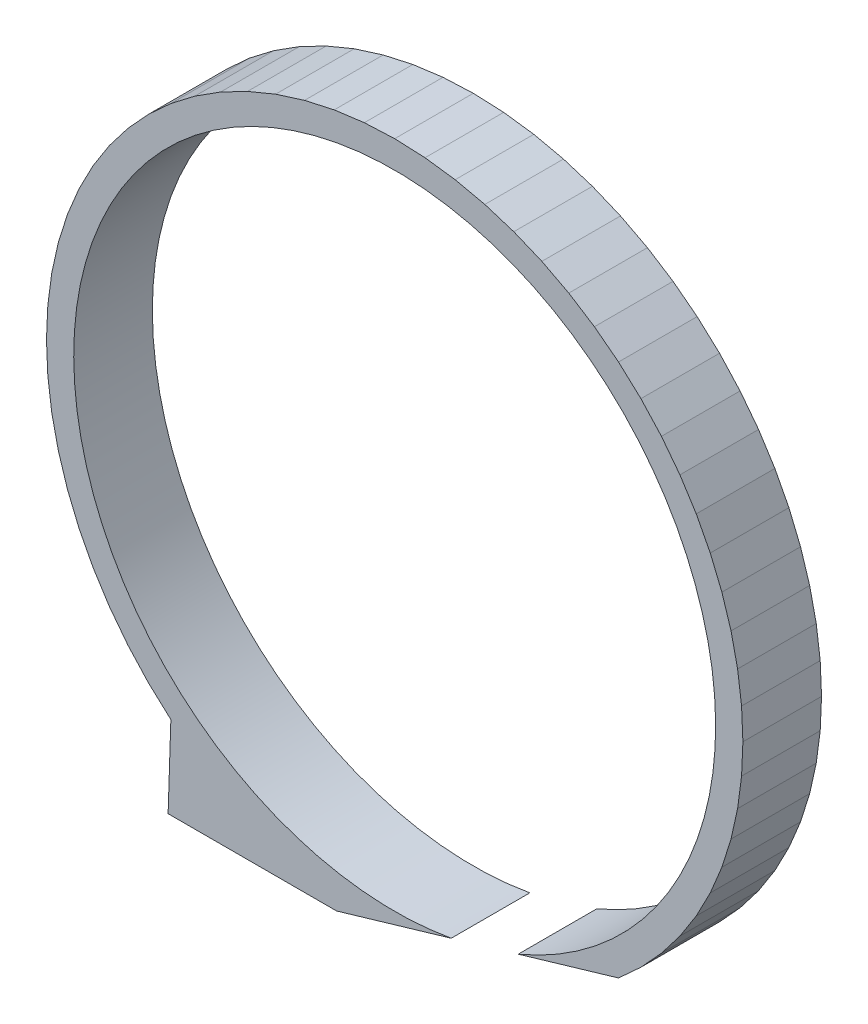
SolidWorks part; units mm, degrees
ref_plane "前视基准面" through (0, 0, 0) normal (0, 0, 1) x (1, 0, 0)
ref_plane "上视基准面" through (0, 0, 0) normal (0, 1, 0) x (1, 0, 0)
ref_plane "右视基准面" through (0, 0, 0) normal (1, 0, 0) x (0, 0, -1)
other "Configuration Table"
sketch "草图1" plane through (0, 0, 0) normal (0, 0, 1) x (1, 0, 0)
  line L0 (39.8528, -47.4948) -> (43.8406, -43.8406)
  line L1 (43.8406, -43.8406) -> (47.4948, -39.8528)
  line L2 (47.4948, -39.8528) -> (50.7874, -35.5617)
  line L3 (50.7874, -35.5617) -> (53.6936, -31)
  line L4 (53.6936, -31) -> (56.1911, -26.2023)
  line L5 (56.1911, -26.2023) -> (58.2609, -21.2052)
  line L6 (58.2609, -21.2052) -> (59.8874, -16.0468)
  line L7 (59.8874, -16.0468) -> (61.0581, -10.7662)
  line L8 (61.0581, -10.7662) -> (61.7641, -5.4037)
  line L9 (61.7641, -5.4037) -> (62, 0)
  line L10 (62, 0) -> (61.7641, 5.4037)
  line L11 (61.7641, 5.4037) -> (61.0581, 10.7662)
  line L12 (61.0581, 10.7662) -> (59.8874, 16.0468)
  line L13 (59.8874, 16.0468) -> (58.2609, 21.2052)
  line L14 (58.2609, 21.2052) -> (56.1911, 26.2023)
  line L15 (56.1911, 26.2023) -> (53.6936, 31)
  line L16 (53.6936, 31) -> (50.7874, 35.5617)
  line L17 (50.7874, 35.5617) -> (47.4948, 39.8528)
  line L18 (47.4948, 39.8528) -> (43.8406, 43.8406)
  line L19 (43.8406, 43.8406) -> (39.8528, 47.4948)
  line L20 (39.8528, 47.4948) -> (35.5617, 50.7874)
  line L21 (35.5617, 50.7874) -> (31, 53.6936)
  line L22 (31, 53.6936) -> (26.2023, 56.1911)
  line L23 (26.2023, 56.1911) -> (21.2052, 58.2609)
  line L24 (21.2052, 58.2609) -> (16.0468, 59.8874)
  line L25 (16.0468, 59.8874) -> (10.7662, 61.0581)
  line L26 (10.7662, 61.0581) -> (5.4037, 61.7641)
  line L27 (5.4037, 61.7641) -> (0, 62)
  line L28 (0, 62) -> (-5.4037, 61.7641)
  line L29 (-5.4037, 61.7641) -> (-10.7662, 61.0581)
  line L30 (-10.7662, 61.0581) -> (-16.0468, 59.8874)
  line L31 (-16.0468, 59.8874) -> (-21.2052, 58.2609)
  line L32 (-21.2052, 58.2609) -> (-26.2023, 56.1911)
  line L33 (-26.2023, 56.1911) -> (-31, 53.6936)
  line L34 (-31, 53.6936) -> (-35.5617, 50.7874)
  line L35 (-35.5617, 50.7874) -> (-39.8528, 47.4948)
  line L36 (-39.8528, 47.4948) -> (-43.8406, 43.8406)
  line L37 (-43.8406, 43.8406) -> (-47.4948, 39.8528)
  line L38 (-47.4948, 39.8528) -> (-50.7874, 35.5617)
  line L39 (-50.7874, 35.5617) -> (-53.6936, 31)
  line L40 (-53.6936, 31) -> (-56.1911, 26.2023)
  line L41 (-56.1911, 26.2023) -> (-58.2609, 21.2052)
  line L42 (-58.2609, 21.2052) -> (-59.8874, 16.0468)
  line L43 (-59.8874, 16.0468) -> (-61.0581, 10.7662)
  line L44 (-61.0581, 10.7662) -> (-61.7641, 5.4037)
  line L45 (-61.7641, 5.4037) -> (-62, 0)
  line L46 (-62, 0) -> (-61.7641, -5.4037)
  line L47 (-61.7641, -5.4037) -> (-61.0581, -10.7662)
  line L48 (-61.0581, -10.7662) -> (-59.8874, -16.0468)
  line L49 (-59.8874, -16.0468) -> (-58.2609, -21.2052)
  line L50 (-58.2609, -21.2052) -> (-56.1911, -26.2023)
  line L51 (-56.1911, -26.2023) -> (-53.6936, -31)
  line L52 (-53.6936, -31) -> (-50.7874, -35.5617)
  line L53 (-50.7874, -35.5617) -> (-47.4948, -39.8528)
  line L54 (-47.4948, -39.8528) -> (-43.8406, -43.8406)
  line L55 (-43.8406, -43.8406) -> (-39.8528, -47.4948)
  line L56 (-39.8528, -47.4948) -> (-40.3415, -62.26)
  line L57 (-40.3415, -62.26) -> (-10.3415, -62.26)
  line L58 (-10.3415, -62.26) -> (39.8528, -47.4948)
  dimension "x0" = 39.8528
  dimension "x1" = 43.8406
  dimension "x2" = 47.4948
  dimension "x3" = 50.7874
  dimension "x4" = 53.6936
  dimension "x5" = 56.1911
  dimension "x6" = 58.2609
  dimension "x7" = 59.8874
  dimension "x8" = 61.0581
  dimension "x9" = 61.7641
  dimension "x10" = 62
  dimension "x11" = 61.7641
  dimension "x12" = 61.0581
  dimension "x13" = 59.8874
  dimension "x14" = 58.2609
  dimension "x15" = 56.1911
  dimension "x16" = 53.6936
  dimension "x17" = 50.7874
  dimension "x18" = 47.4948
  dimension "x19" = 43.8406
  dimension "x20" = 39.8528
  dimension "x21" = 35.5617
  dimension "x22" = 31
  dimension "x23" = 26.2023
  dimension "x24" = 21.2052
  dimension "x25" = 16.0468
  dimension "x26" = 10.7662
  dimension "x27" = 5.4037
  dimension "x29" = 5.4037
  dimension "x30" = 10.7662
  dimension "x31" = 16.0468
  dimension "x32" = 21.2052
  dimension "x33" = 26.2023
  dimension "x34" = 31
  dimension "x35" = 35.5617
  dimension "x36" = 39.8528
  dimension "x37" = 43.8406
  dimension "x38" = 47.4948
  dimension "x39" = 50.7874
  dimension "x40" = 53.6936
  dimension "x41" = 56.1911
  dimension "x42" = 58.2609
  dimension "x43" = 59.8874
  dimension "x44" = 61.0581
  dimension "x45" = 61.7641
  dimension "x46" = 62
  dimension "x47" = 61.7641
  dimension "x48" = 61.0581
  dimension "x49" = 59.8874
  dimension "x50" = 58.2609
  dimension "x51" = 56.1911
  dimension "x52" = 53.6936
  dimension "x53" = 50.7874
  dimension "x54" = 47.4948
  dimension "x55" = 43.8406
  dimension "x56" = 39.8528
  dimension "x57" = 40.3415
  dimension "x58" = 10.3415
  dimension "y0" = 47.4948
  dimension "y1" = 43.8406
  dimension "y2" = 39.8528
  dimension "y3" = 35.5617
  dimension "y4" = 31
  dimension "y5" = 26.2023
  dimension "y6" = 21.2052
  dimension "y7" = 16.0468
  dimension "y8" = 10.7662
  dimension "y9" = 5.4037
  dimension "y11" = 5.4037
  dimension "y12" = 10.7662
  dimension "y13" = 16.0468
  dimension "y14" = 21.2052
  dimension "y15" = 26.2023
  dimension "y16" = 31
  dimension "y17" = 35.5617
  dimension "y18" = 39.8528
  dimension "y19" = 43.8406
  dimension "y20" = 47.4948
  dimension "y21" = 50.7874
  dimension "y22" = 53.6936
  dimension "y23" = 56.1911
  dimension "y24" = 58.2609
  dimension "y25" = 59.8874
  dimension "y26" = 61.0581
  dimension "y27" = 61.7641
  dimension "y28" = 62
  dimension "y29" = 61.7641
  dimension "y30" = 61.0581
  dimension "y31" = 59.8874
  dimension "y32" = 58.2609
  dimension "y33" = 56.1911
  dimension "y34" = 53.6936
  dimension "y35" = 50.7874
  dimension "y36" = 47.4948
  dimension "y37" = 43.8406
  dimension "y38" = 39.8528
  dimension "y39" = 35.5617
  dimension "y40" = 31
  dimension "y41" = 26.2023
  dimension "y42" = 21.2052
  dimension "y43" = 16.0468
  dimension "y44" = 10.7662
  dimension "y45" = 5.4037
  dimension "y47" = 5.4037
  dimension "y48" = 10.7662
  dimension "y49" = 16.0468
  dimension "y50" = 21.2052
  dimension "y51" = 26.2023
  dimension "y52" = 31
  dimension "y53" = 35.5617
  dimension "y54" = 39.8528
  dimension "y55" = 43.8406
  dimension "y56" = 47.4948
  dimension "y57" = 62.26
extrude "Clamp_and_lower_foot" add sketch "草图1" along normal blind 14
sketch "草图2" plane through (0, 0, 14) normal (0, 0, 1) x (1, 0, 0)
  circle A0 centre (0, 0) radius 57.15
  dimension "diameter" = 114.3
extrude "Canister_seat" cut sketch "草图2" against normal through all
